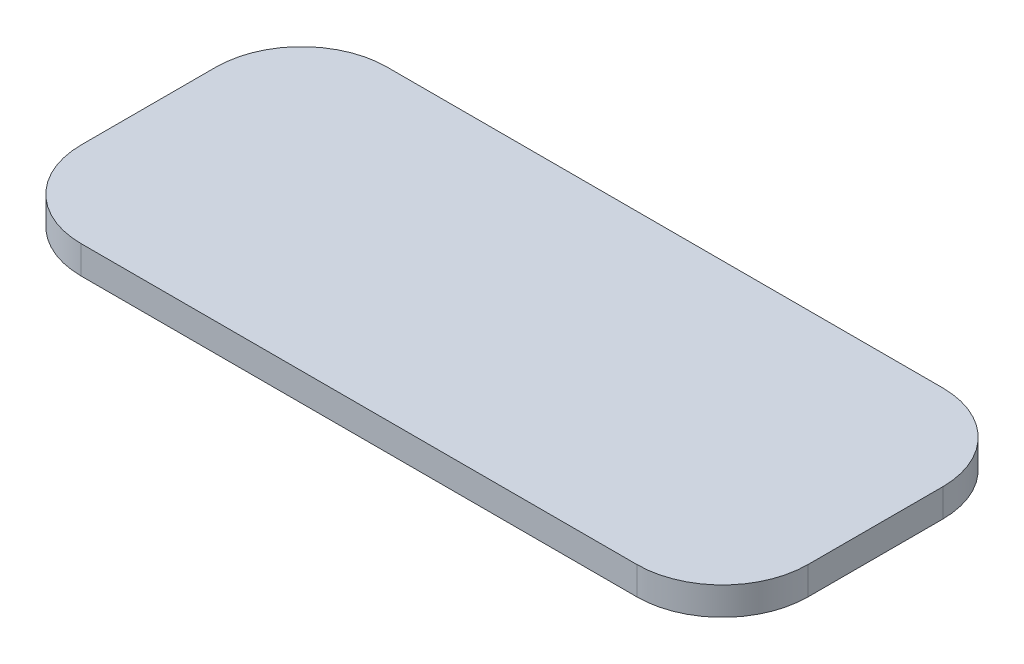
SolidWorks part; units mm, degrees
ref_plane "前视基准面" through (0, 0, 0) normal (0, 0, 1) x (1, 0, 0)
ref_plane "上视基准面" through (0, 0, 0) normal (0, 1, 0) x (1, 0, 0)
ref_plane "右视基准面" through (0, 0, 0) normal (1, 0, 0) x (0, 0, -1)
sketch "草图1" plane through (0, 0, 0) normal (0, 1, 0) x (1, 0, 0)
  line L1 (-25.9, 10.9) -> (25.9, 10.9)
  line L2 (-25.9, 10.9) -> (-25.9, -10.9)
  line L3 (-25.9, -10.9) -> (25.9, -10.9)
  line L4 (25.9, 10.9) -> (25.9, -10.9)
  line L5 (-25.9, 10.9) -> (25.9, -10.9) construction
  line L6 (-25.9, -10.9) -> (25.9, 10.9) construction
  point P0 (0, 0)
  dimension "D1" = 21.8
  dimension "D2" = 51.8
extrude "凸台-拉伸1" add sketch "草图1" along normal blind 2
fillet "圆角1" radius 6.1 4 edges at (-25.9, 1, 10.9) (-25.9, 1, -10.9) (25.9, 1, -10.9) (25.9, 1, 10.9)
